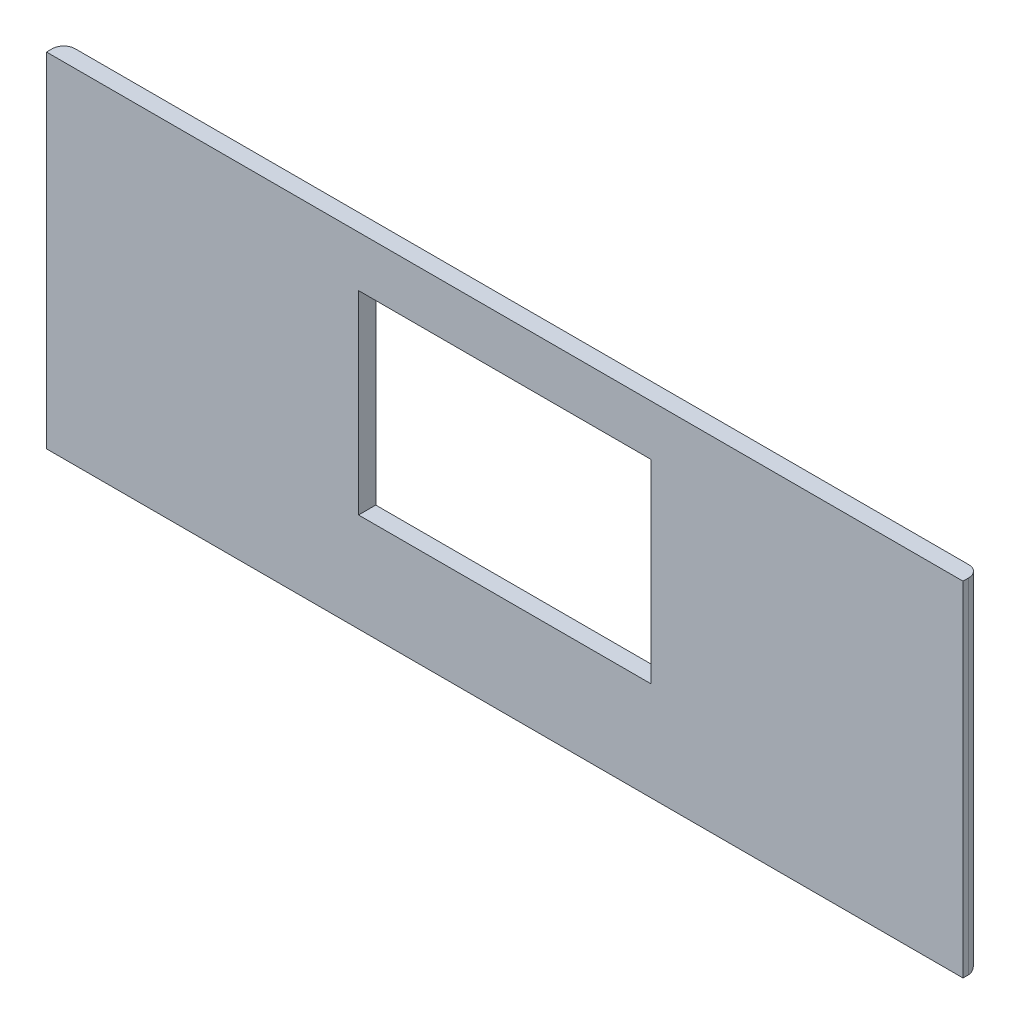
SolidWorks part; units mm, degrees
ref_plane "Front Plane" through (0, 0, 0) normal (0, 0, 1) x (1, 0, 0)
ref_plane "Top Plane" through (0, 0, 0) normal (0, 1, 0) x (1, 0, 0)
ref_plane "Right Plane" through (0, 0, 0) normal (1, 0, 0) x (0, 0, -1)
sketch "Sketch1" plane through (0, 0, 0) normal (0, 0, 1) x (1, 0, 0)
  line L1 (0, 0) -> (160, 0)
  line L2 (0, 0) -> (0, 60)
  line L3 (0, 60) -> (160, 60)
  line L4 (160, 0) -> (160, 60)
  dimension "D1" = 160
  dimension "D2" = 60
extrude "Boss-Extrude1" add sketch "Sketch1" along normal blind 3
sketch "Sketch2" plane through (0, 0, 0) normal (0, 0, -1) x (-1, 0, 0)
  line L0 (-55.4766, 18.2417) -> (-55.4766, 50.1705) construction
  line L1 (-104.5234, 18.2417) -> (-55.4766, 18.2417) construction
  line L2 (-104.5234, 50.1705) -> (-104.5234, 18.2417) construction
  line L3 (-55.4766, 50.1705) -> (-104.5234, 50.1705) construction
  line L4 (-55.4766, 18.2417) -> (-55.4766, 50.1705) construction
  line L5 (-104.5234, 18.2417) -> (-55.4766, 18.2417) construction
  line L6 (-104.5234, 50.1705) -> (-104.5234, 18.2417) construction
  line L7 (-55.4766, 50.1705) -> (-104.5234, 50.1705) construction
  line L9 (-105.5234, 51.1705) -> (-54.4766, 51.1705)
  line L10 (-105.5234, 51.1705) -> (-105.5234, 17.2417)
  line L11 (-105.5234, 17.2417) -> (-54.4766, 17.2417)
  line L12 (-54.4766, 51.1705) -> (-54.4766, 17.2417)
  dimension "D1" = 1
  dimension "D2" = 1
  dimension "D3" = 1
  dimension "D4" = 1
extrude "Cut-Extrude1" cut sketch "Sketch2" against normal through all
fillet "Fillet1" radius 2 3 edges at (80, 0, 0) (0, 30, 0) (160, 30, 0)
